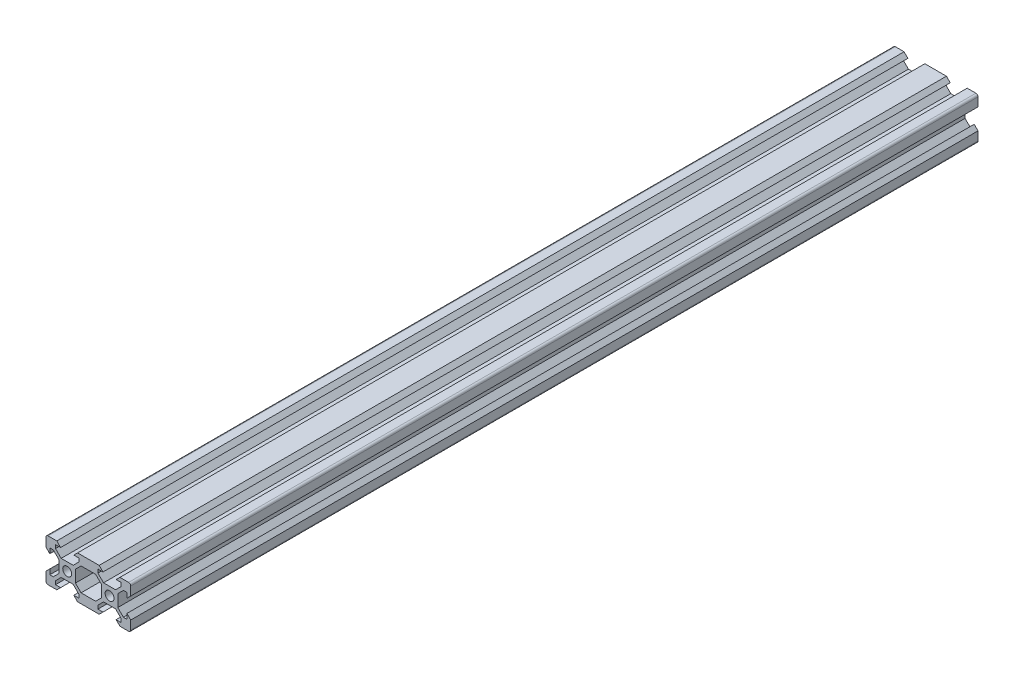
SolidWorks part; units mm, degrees
ref_plane "Front (XY)" through (0, 0, 0) normal (0, 0, 1) x (1, 0, 0)
ref_plane "Top (XZ)" through (0, 0, 0) normal (0, 1, 0) x (1, 0, 0)
ref_plane "Right (YZ)" through (0, 0, 0) normal (1, 0, 0) x (0, 0, -1)
sketch "Sketch2" plane through (0, 0, 0) normal (0, 0, 1) x (1, 0, 0)
  line L0 (-10, 10) -> (10, 10)
  line L1 (10, 10) -> (10, -10)
  line L2 (10, -10) -> (-10, -10)
  line L3 (-10, -10) -> (-10, 10)
  point P4 (0, -10)
  point P6 (10, 0)
  dimension "D1" = 20
  dimension "D2" = 20
extrude "Boss-Extrude1" add sketch "Sketch2" against normal blind 400
sketch "Sketch3" plane through (0, 0, 0) normal (0, 0, 1) x (1, 0, 0)
  line L0 (0, 0) -> (0, 10) construction
  line L1 (0, 10) -> (-3.1, 10) construction
  line L2 (10, 10) -> (-10, 10) construction
  line L3 (-3.1, 10) -> (-3.1, 8.2) construction
  line L4 (3.1, 10) -> (3.1, 8.2) construction
  line L5 (-3.1, 8.2) -> (-4.9, 10)
  line L6 (3.1, 8.2) -> (4.9, 10)
  line L7 (-3.1, 8.2) -> (-5.5, 8.2)
  line L8 (3.1, 8.2) -> (5.5, 8.2)
  line L9 (-5.5, 8.2) -> (-5.5, 6.56)
  line L10 (5.5, 8.2) -> (5.5, 6.56)
  line L11 (0, 10) -> (0, 3.9) construction
  line L12 (2.84, 3.9) -> (-2.84, 3.9)
  line L13 (-2.84, 3.9) -> (-5.5, 6.56)
  line L14 (2.84, 3.9) -> (5.5, 6.56)
  line L15 (-4.9, 10) -> (4.9, 10)
  point P21 (0, 3.9)
  dimension "D1" = 3.1
  dimension "D2" = 1.8
  dimension "D3" = 90
  dimension "D4" = 2.4
  dimension "D5" = 1.64
  dimension "D6" = 6.1
  dimension "D7" = 5.68
extrude "Cut-Extrude1" cut sketch "Sketch3" along normal through all and the other way through all
sketch "Sketch8" plane through (0, 0, 0) normal (1, 0, 0) x (0, 0, -1)
  line L0 (0, 0) -> (-11.2124, 0) construction
  line L1 (0, -10) -> (0, 10) construction
pattern_circular "CirPattern2" count 4 over 360 about axis through (0, 0, 0) along (0, 0, 1) of "Cut-Extrude1"
sketch "Sketch9" plane through (0, 0, 0) normal (0, 0, 1) x (1, 0, 0)
  circle A0 centre (0, 0) radius 2.1
  dimension "D1" = 4.2
extrude "Cut-Extrude2" cut sketch "Sketch9" against normal through all
mirror "Mirror1" about plane through (10, 10, -400) normal (1, 0, 0) of "Cut-Extrude2", "CirPattern2", "Cut-Extrude1", "Boss-Extrude1"
sketch "Sketch10" plane through (0, 0, 0) normal (0, 0, 1) x (1, 0, 0)
  line L0 (13.44, -5.5) -> (11.8, -5.5) construction
  line L1 (6.56, -5.5) -> (8.2, -5.5) construction
  line L2 (11.8, 5.5) -> (13.44, 5.5) construction
  line L3 (8.2, 5.5) -> (6.56, 5.5) construction
  line L4 (13.44, -5.5) -> (11.8, -5.5)
  line L5 (6.56, -5.5) -> (8.2, -5.5)
  line L6 (11.8, 5.5) -> (13.44, 5.5)
  line L7 (8.2, 5.5) -> (6.56, 5.5)
  line L8 (13.44, 5.5) -> (13.44, -5.5)
  line L9 (11.8, -5.5) -> (8.2, -5.5)
  line L10 (6.56, -5.5) -> (6.56, 5.5)
  line L11 (8.2, 5.5) -> (11.8, 5.5)
extrude "Cut-Extrude3" cut sketch "Sketch10" against normal through all
fillet "Fillet1" radius 1 4 edges at (30, 10, -200) (30, -10, -200) (-10, -10, -200) (-10, 10, -200)
